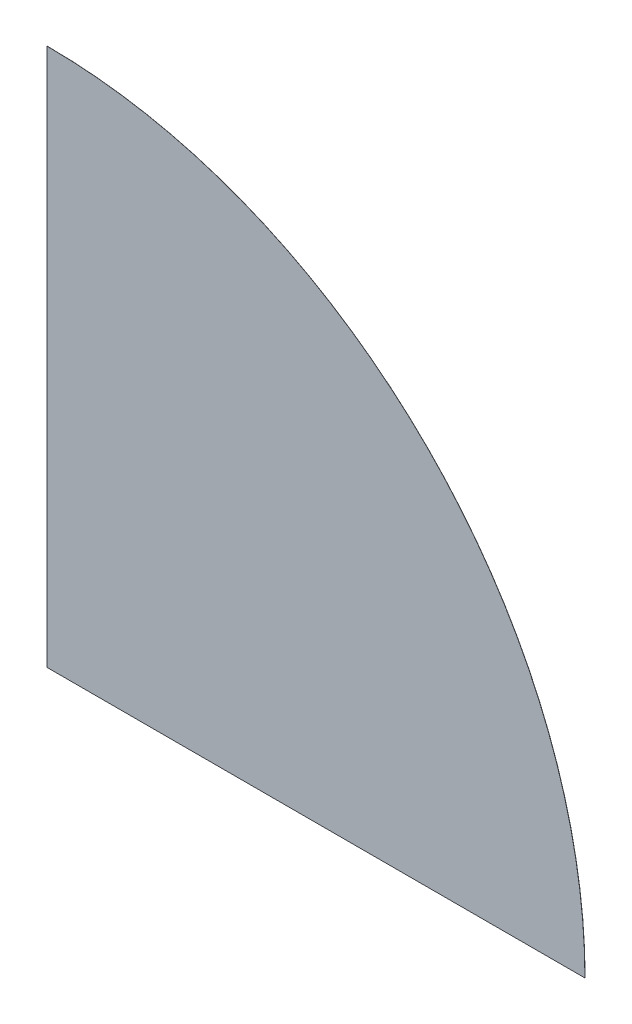
SolidWorks part; units mm, degrees
ref_plane "Front Plane" through (0, 0, 0) normal (0, 0, 1) x (1, 0, 0)
ref_plane "Top Plane" through (0, 0, 0) normal (0, 1, 0) x (1, 0, 0)
ref_plane "Right Plane" through (0, 0, 0) normal (1, 0, 0) x (0, 0, -1)
sketch "Sketch1" plane through (0, 0, 0) normal (0, 0, 1) x (1, 0, 0)
  line L1 (0, 0) -> (3.57, 0)
  line L2 (0, 3.57) -> (0, 0)
  arc A0 (3.57, 0) -> (0, 3.57) centre (0, 0) ccw
  point P6 (0, 0)
  dimension "D1" = 3.57
extrude "Boss-Extrude1" add sketch "Sketch1" along normal blind 0.001
